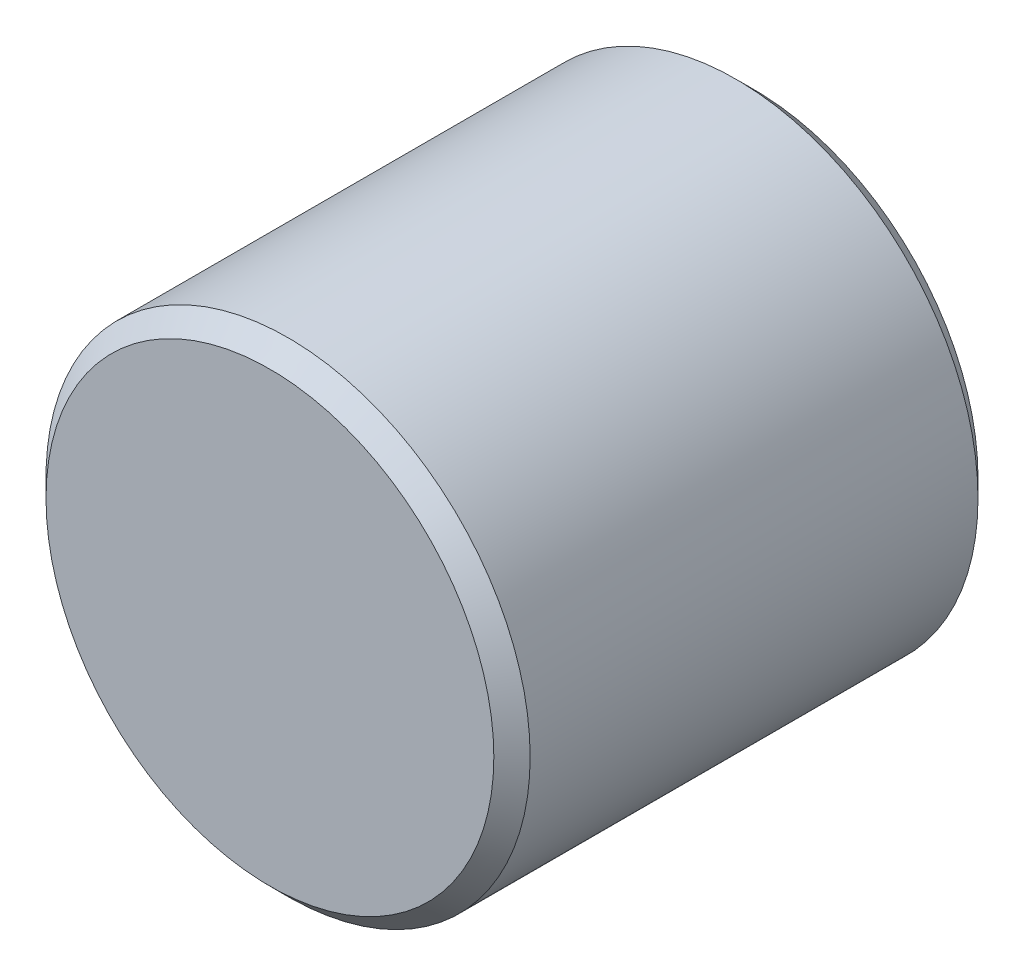
SolidWorks part; units mm, degrees
material "Ст3пс ГОСТ 380-2005"
ref_plane "Front" through (0, 0, 0) normal (0, 0, 1) x (1, 0, 0)
ref_plane "Top" through (0, 0, 0) normal (0, 1, 0) x (1, 0, 0)
ref_plane "Right" through (0, 0, 0) normal (1, 0, 0) x (0, 0, -1)
sketch "Эскиз1" plane through (0, 0, 0) normal (0, 0, 1) x (1, 0, 0)
  circle A0 centre (0, 0) radius 4
  dimension "D1" = 8
extrude "Бобышка-Вытянуть1" add sketch "Эскиз1" along normal blind 8
chamfer "Фаска1" distance 0.3 angle 45 2 edges at (4, 0, 0) (4, 0, 8)
